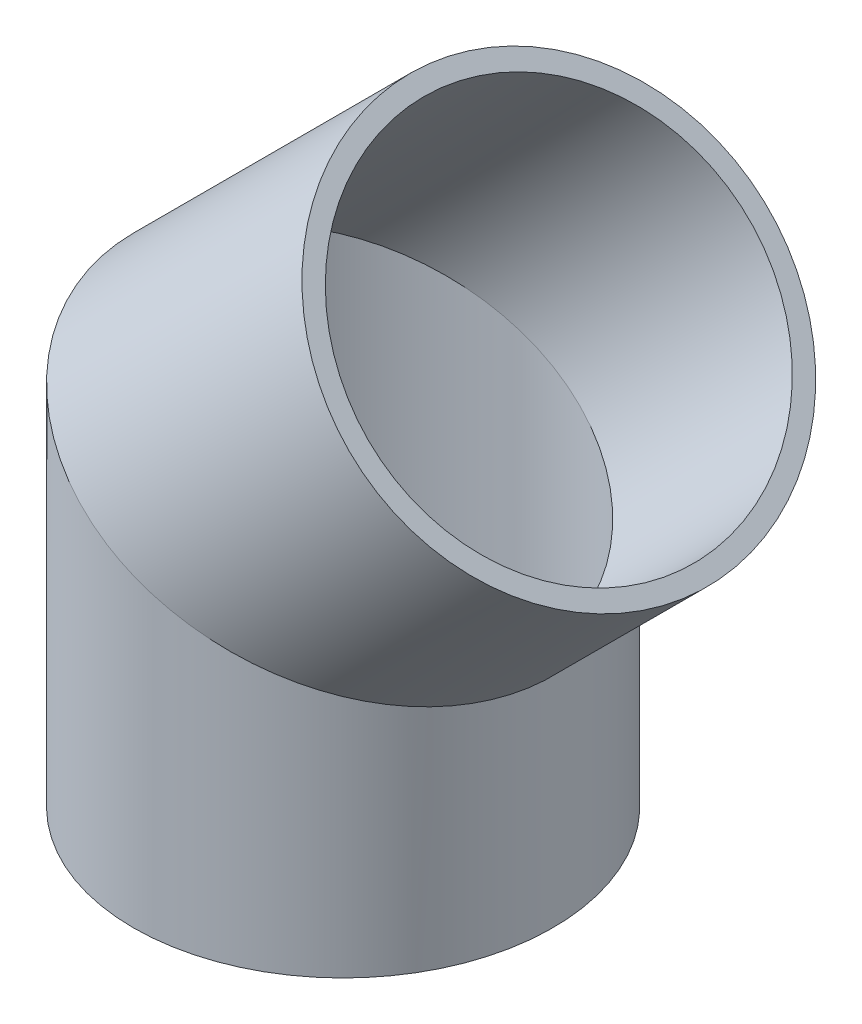
SolidWorks part; units mm, degrees
ref_plane "前视基准面" through (0, 0, 0) normal (0, 0, 1) x (1, 0, 0)
ref_plane "上视基准面" through (0, 0, 0) normal (0, 1, 0) x (1, 0, 0)
ref_plane "右视基准面" through (0, 0, 0) normal (1, 0, 0) x (0, 0, -1)
sketch "草图1" plane through (0, 0, 0) normal (0, 1, 0) x (1, 0, 0)
  circle A0 centre (0, 0) radius 27.5
  circle A1 centre (0, 0) radius 25
  dimension "D1" = 55
  dimension "D2" = 50
sketch "草图2" plane through (0, 0, 0) normal (0, 0, 1) x (1, 0, 0)
  line L0 (0, 0) -> (0, 40)
  line L1 (0, 40) -> (28.2843, 68.2843)
  dimension "D1" = 40
  dimension "D2" = 40
  dimension "D3" = 135
sweep "扫描1" add profiles "草图1" path "草图2"
